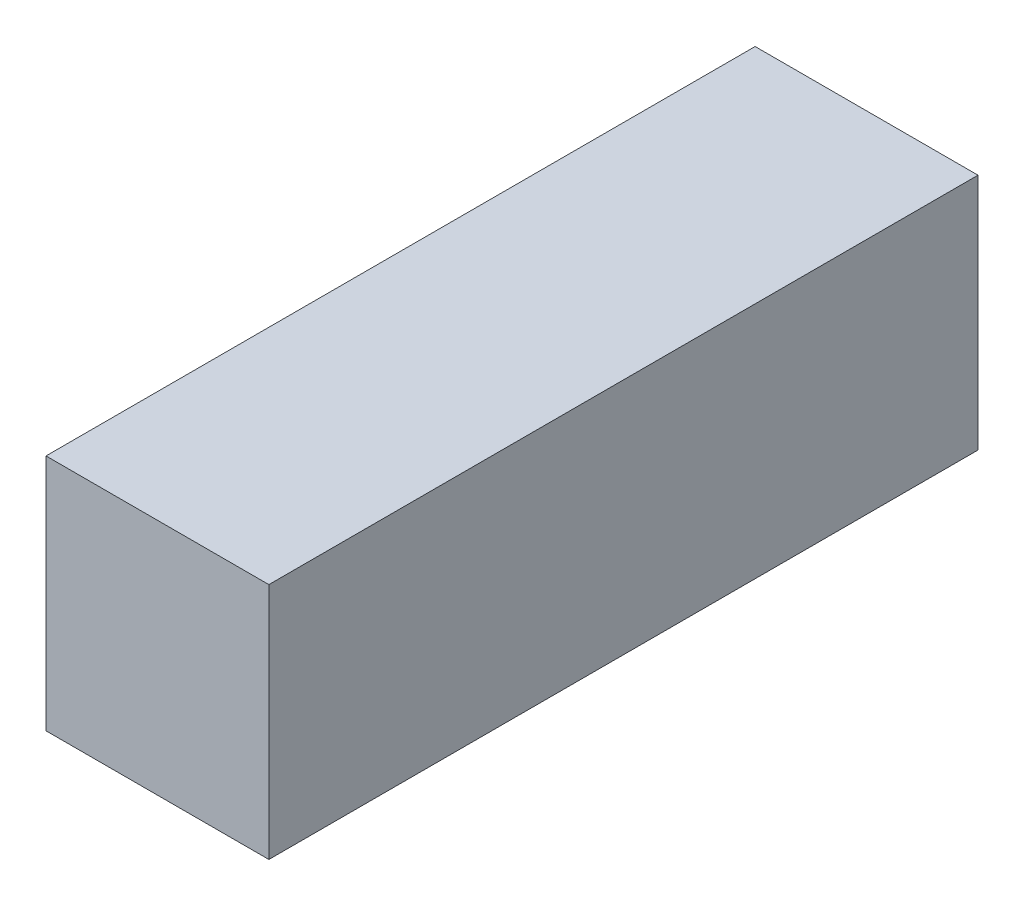
SolidWorks part; units mm, degrees
ref_plane "Front Plane" through (0, 0, 0) normal (0, 0, 1) x (1, 0, 0)
ref_plane "Top Plane" through (0, 0, 0) normal (0, 1, 0) x (1, 0, 0)
ref_plane "Right Plane" through (0, 0, 0) normal (1, 0, 0) x (0, 0, -1)
sketch "Sketch1" plane through (0, 0, 0) normal (0, 0, 1) x (1, 0, 0)
  line L1 (0, 0) -> (44, 0)
  line L2 (0, 0) -> (0, 47)
  line L3 (0, 47) -> (44, 47)
  line L4 (44, 0) -> (44, 47)
  dimension "D1" = 47
  dimension "D2" = 44
extrude "Boss-Extrude1" add sketch "Sketch1" along normal blind 140
